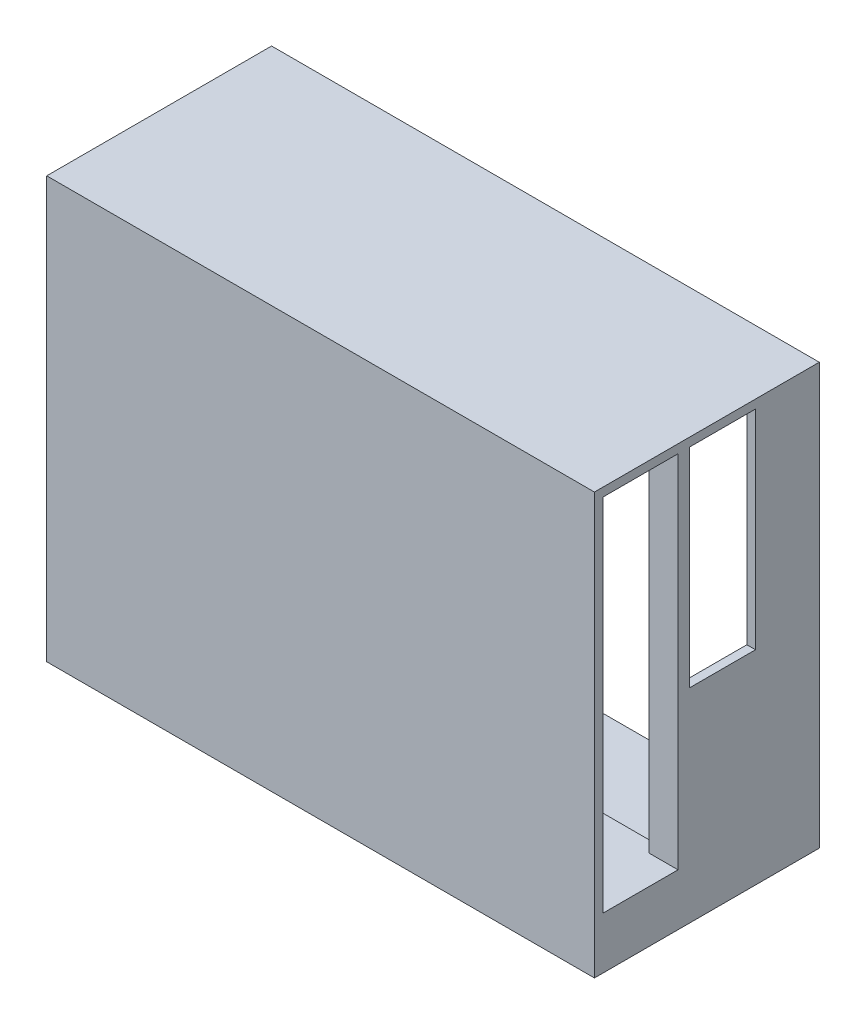
SolidWorks part; units mm, degrees
ref_plane "Plan de face" through (0, 0, 0) normal (0, 0, 1) x (1, 0, 0)
ref_plane "Plan de dessus" through (0, 0, 0) normal (0, 1, 0) x (1, 0, 0)
ref_plane "Plan de droite" through (0, 0, 0) normal (1, 0, 0) x (0, 0, -1)
sketch "Esquisse3" plane through (0, 0, 0) normal (0, 0, 1) x (1, 0, 0)
  line L1 (95, 73) -> (-95, 73)
  line L2 (95, 73) -> (95, -73)
  line L3 (95, -73) -> (-95, -73)
  line L4 (-95, 73) -> (-95, -73)
  line L5 (95, 73) -> (-95, -73) construction
  line L6 (95, -73) -> (-95, 73) construction
  point P0 (0, 0)
  dimension "D1" = 146
  dimension "D2" = 190
extrude "Boss.-Extru.3" add sketch "Esquisse3" along normal blind 3
sketch "Esquisse4" plane through (0, 0, 0) normal (0, 0, -1) x (-1, 0, 0)
  line L0 (95, 73) -> (95, -73) construction
  line L1 (-95, -73) -> (95, -73)
  line L2 (-95, -73) -> (-95, -70)
  line L3 (-95, -70) -> (95, -70)
  line L4 (95, -73) -> (95, -70)
  dimension "D1" = 3
extrude "Boss.-Extru.4" add sketch "Esquisse4" along normal blind 75
sketch "Esquisse5" plane through (0, 0, 0) normal (0, 0, -1) x (-1, 0, 0)
  line L0 (0, 0) -> (95, 0) construction
  line L1 (95, 73) -> (95, -70) construction
  line L2 (95, 0) -> (-95, 0) construction
  line L3 (-95, -70) -> (-95, 73) construction
  line L5 (-95, 73) -> (95, 73)
  line L6 (-95, 73) -> (-95, 70)
  line L7 (-95, 70) -> (95, 70)
  line L8 (95, 73) -> (95, 70)
  dimension "D1" = 3
extrude "Boss.-Extru.5" add sketch "Esquisse5" along normal blind 75
sketch "Esquisse6" plane through (0, 0, 0) normal (0, 0, -1) x (-1, 0, 0)
  line L0 (-95, 70) -> (95, 70) construction
  line L1 (95, -70) -> (92, -70)
  line L2 (95, -70) -> (95, 70)
  line L3 (95, 70) -> (92, 70)
  line L4 (92, -70) -> (92, 70)
  dimension "D1" = 3
extrude "Boss.-Extru.6" add sketch "Esquisse6" along normal blind 75
sketch "Esquisse7" plane through (0, 0, 0) normal (0, 0, -1) x (-1, 0, 0)
  line L0 (-95, 70) -> (92, 70) construction
  line L1 (-95, -70) -> (-92, -70)
  line L2 (-95, -70) -> (-95, 70)
  line L3 (-95, 70) -> (-92, 70)
  line L4 (-92, -70) -> (-92, 70)
  dimension "D1" = 3
extrude "Boss.-Extru.7" add sketch "Esquisse7" along normal blind 75
sketch "Esquisse8" plane through (92, 0, 0) normal (-1, 0, 0) x (0, 0, 1)
  line L0 (-75, 70) -> (0, 70) construction
  line L1 (0, -70) -> (-26, -70)
  line L2 (0, -70) -> (0, 70)
  line L3 (0, 70) -> (-26, 70)
  line L4 (-26, -70) -> (-26, 70)
  dimension "D1" = 26
extrude "Enlèv. mat.-Extru.1" cut sketch "Esquisse8" against normal blind 5
sketch "Esquisse9" plane through (0, 0, 0) normal (0, 0, -1) x (-1, 0, 0)
  line L1 (92, 70) -> (42, 70)
  line L2 (92, 70) -> (92, 56.4195)
  line L3 (92, 56.4195) -> (42, 56.4195)
  line L4 (42, 70) -> (42, 56.4195)
  dimension "D1" = 50
extrude "Boss.-Extru.8" add sketch "Esquisse9" along normal blind 30
sketch "Esquisse10" plane through (0, 0, 0) normal (0, 0, -1) x (-1, 0, 0)
  line L0 (92, -70) -> (-95, -70) construction
  line L1 (42, 56.4195) -> (47, 56.4195)
  line L2 (42, 56.4195) -> (42, -70)
  line L3 (42, -70) -> (47, -70)
  line L4 (47, 56.4195) -> (47, -70)
  dimension "D1" = 5
extrude "Boss.-Extru.9" add sketch "Esquisse10" along normal blind 30
sketch "Esquisse12" plane through (0, 0, -30) normal (0, 0, -1) x (-1, 0, 0)
  line L0 (92, 56.4195) -> (47, 56.4195)
  line L1 (92, 56.4195) -> (92, -59.6426)
  line L2 (47, 56.4195) -> (47, -59.6426)
  line L3 (92, -59.6426) -> (47, -59.6426)
extrude "Boss.-Extru.10" add sketch "Esquisse12" against normal blind 5
sketch "Esquisse13" plane through (0, 0, 0) normal (0, 0, -1) x (-1, 0, 0)
  line L0 (42, 70) -> (42, -70) construction
  line L1 (42, -55) -> (-95, -55)
  line L2 (42, -55) -> (42, -60)
  line L3 (42, -60) -> (-95, -60)
  line L4 (-95, -55) -> (-95, -60)
  line L5 (-95, -70) -> (-95, 70) construction
  line L6 (42, -70) -> (-95, -70) construction
  dimension "D1" = 10
  dimension "D2" = 5
extrude "Boss.-Extru.11" add sketch "Esquisse13" along normal blind 30
sketch "Esquisse14" plane through (0, 0, -30) normal (0, 0, -1) x (-1, 0, 0)
  line L1 (-92, -60) -> (42, -60)
  line L2 (-92, -60) -> (-92, -70)
  line L3 (-92, -70) -> (42, -70)
  line L4 (42, -60) -> (42, -70)
extrude "Boss.-Extru.12" add sketch "Esquisse14" against normal up to surface (4 mm away) up to face at (93.5, -65, -26)
sketch "Esquisse15" plane through (95, 0, 0) normal (1, 0, 0) x (0, 0, -1)
  line L1 (26, -60) -> (0, -60)
  line L2 (26, -60) -> (26, -70)
  line L3 (26, -70) -> (0, -70)
  line L4 (0, -60) -> (0, -70)
extrude "Boss.-Extru.13" add sketch "Esquisse15" against normal blind 5
sketch "Esquisse16" plane through (92, 0, 0) normal (-1, 0, 0) x (0, 0, 1)
  line L1 (-30, -55) -> (-26, -55)
  line L2 (-30, -55) -> (-30, 70)
  line L3 (-30, 70) -> (-26, 70)
  line L4 (-26, -55) -> (-26, 70)
extrude "Boss.-Extru.14" add sketch "Esquisse16" along normal blind 7
sketch "Esquisse17" plane through (92, 0, 0) normal (-1, 0, 0) x (0, 0, 1)
  line L1 (-30, 70) -> (-52.881, 70)
  line L2 (-30, 70) -> (-30, -2.3224)
  line L3 (-30, -2.3224) -> (-52.881, -2.3224)
  line L4 (-52.881, 70) -> (-52.881, -2.3224)
extrude "Enlèv. mat.-Extru.2" cut sketch "Esquisse17" against normal up to surface (3 mm away) up to face at (95, 7.5, -13)
sketch "Esquisse19" plane through (0, 0, -30) normal (0, 0, -1) x (-1, 0, 0)
  line L1 (47, -59.6426) -> (91.9999, -59.6426)
  line L2 (47, -59.6426) -> (47, -70.1273)
  line L3 (47, -70.1273) -> (91.9999, -70.1273)
  line L4 (91.9999, -59.6426) -> (91.9999, -70.1273)
extrude "Boss.-Extru.15" add sketch "Esquisse19" against normal blind 3
